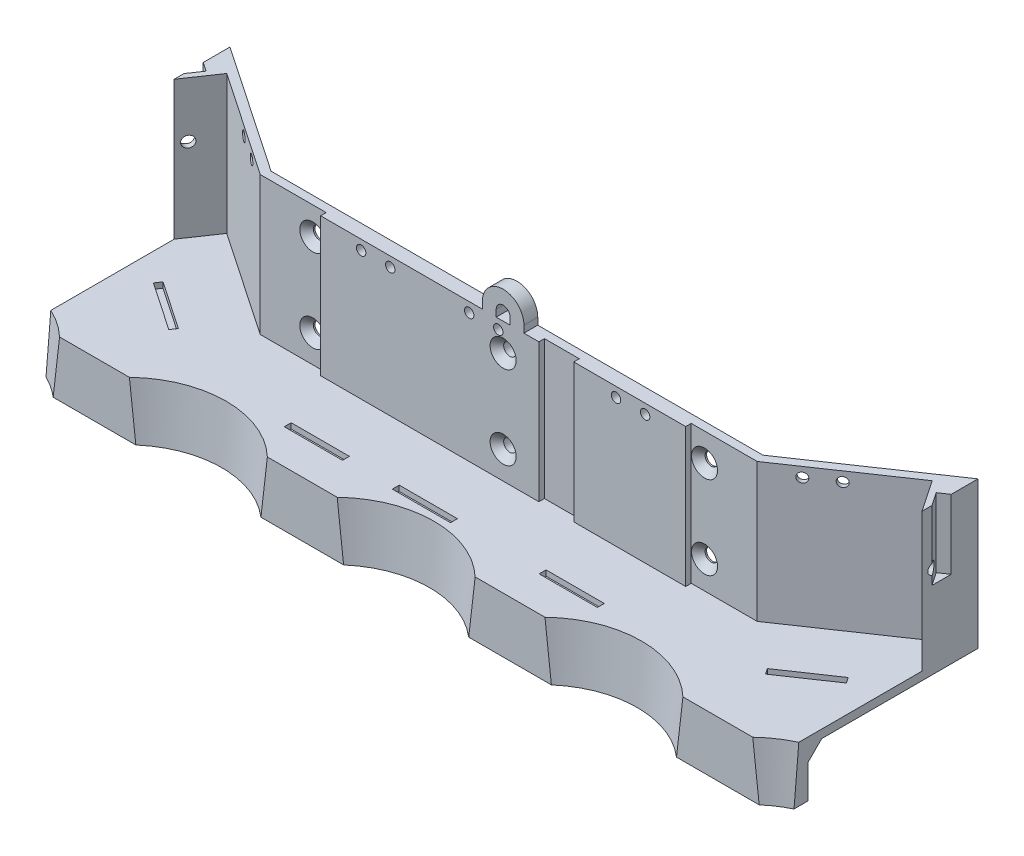
SolidWorks part; units mm, degrees
ref_plane "Front Plane" through (0, 0, 0) normal (0, 0, 1) x (1, 0, 0)
ref_plane "Top Plane" through (0, 0, 0) normal (0, 1, 0) x (1, 0, 0)
ref_plane "Right Plane" through (0, 0, 0) normal (1, 0, 0) x (0, 0, -1)
sketch "Sketch1" plane through (0, 0, 0) normal (1, 0, 0) x (0, 0, -1)
  line L0 (0, 0) -> (0, 53)
  line L1 (0, 53) -> (-3, 53)
  line L2 (-3, 53) -> (-3, 3)
  line L3 (-3, 3) -> (-40, 3)
  line L4 (-40, 3) -> (-40, 0)
  line L5 (-25, 0) -> (0, 0)
  line L6 (-40, 0) -> (-40, -17)
  line L7 (-40, -17) -> (-30, -17)
  line L9 (-25, 0) -> (-30, -5)
  line L10 (-30, -5) -> (-30, -17)
  dimension "D1" = 3
  dimension "D2" = 3
  dimension "D3" = 40
  dimension "D4" = 50
  dimension "D5" = 20
  dimension "D6" = 10
  dimension "D7" = 15
  dimension "D8" = 45
extrude "Boss-Extrude1" add sketch "Sketch1" along normal mid plane 270
sketch "Sketch2" plane through (0, 0, 0) normal (1, 0, 0) x (0, 0, -1)
  line L0 (-66, 3) -> (-66, -112) construction
  line L1 (-66, 3) -> (-30, 3)
  line L2 (-3, 3) -> (-40, 3) construction
  line L3 (-30, 3) -> (-39, -112)
  line L4 (-39, -112) -> (-66, -112)
  line L5 (-40, 3) -> (-40, -17) construction
  line L6 (-66, 3) -> (-66, -112)
  dimension "D1" = 54
  dimension "D2" = 72
  dimension "D3" = 115
  dimension "D4" = 10
revolve "Cut-Revolve1" cut sketch "Sketch2" angle 360 about L0
ref_plane "Plane1" through (75, 0, 0) normal (1, 0, 0) x (0, 0, -1)
sketch "Sketch3" plane through (75, 0, 0) normal (1, 0, 0) x (0, 0, -1)
  line L4 (-30, 3) -> (-66, 3)
  line L5 (-39, -112) -> (-30, 3)
  line L6 (-66, -112) -> (-39, -112)
  line L7 (-66, 3) -> (-66, -112)
  line L8 (-30, 3) -> (-66, 3)
  line L9 (-39, -112) -> (-30, 3)
  line L10 (-66, -112) -> (-39, -112)
  line L11 (-66, 3) -> (-66, -112)
  dimension "D1" = 0
revolve "Cut-Revolve2" cut sketch "Sketch3" angle 360 about L11
ref_plane "Plane2" through (150, 0, 0) normal (1, 0, 0) x (0, 0, -1)
sketch "Sketch4" plane through (150, 0, 0) normal (1, 0, 0) x (0, 0, -1)
  line L8 (-30, 3) -> (-66, 3)
  line L9 (-66, 3) -> (-66, -112)
  line L10 (-66, -112) -> (-39, -112)
  line L11 (-39, -112) -> (-30, 3)
  line L12 (-30, 3) -> (-66, 3)
  line L13 (-66, 3) -> (-66, -112)
  line L14 (-66, -112) -> (-39, -112)
  line L15 (-39, -112) -> (-30, 3)
  dimension "D1" = 0
revolve "Cut-Revolve3" cut sketch "Sketch4" angle 360 about L13
sketch "Sketch5" plane through (0, 3, 0) normal (0, 1, 0) x (1, 0, 0)
  line L0 (135, -3) -> (135, 27.7803)
  line L1 (135, -3) -> (135, -33.2739) construction
  line L2 (135, 27.7803) -> (77.0996, -11.5585) construction
  line L3 (77.0996, -11.5585) -> (77.0996, -3)
  line L4 (135, -3) -> (-135, -3) construction
  line L5 (77.0996, -3) -> (135, -3)
  line L6 (129.7686, -36.2226) -> (84.4272, -67.0285) construction
  line L7 (77.0996, -11.5585) -> (89.6963, -3)
  line L8 (84.3581, -3) -> (135, 31.4072)
  line L9 (135, 31.4072) -> (135, 27.7803)
  arc A0 (135, -33.2739) -> (125.1002, -40) centre (150, -66) ccw construction
  line M16 (135, -3) -> (-135, -3)
  dimension "D1" = 70
  dimension "D2" = 50
  dimension "D3" = 3
extrude "Boss-Extrude2" add sketch "Sketch5" along normal up to surface and the other way up to surface contours L0 L2 M16
sketch "Sketch7" plane through (0, 3, 0) normal (0, 1, 0) x (1, 0, 0)
  line L0 (89.6963, -3) -> (135, 27.7803)
  line L1 (135, 31.4072) -> (135, -3) construction
  line L2 (135, 27.7803) -> (135, -3)
  line L3 (135, -3) -> (89.6963, -3)
  line L5 (135, 31.4072) -> (88.7736, 0) construction
  dimension "D1" = 3
extrude "Cut-Extrude1" cut sketch "Sketch7" along normal up to surface (50 mm away) up to face at (17.7547, 53, -5.0814)
sketch "Sketch8" plane through (0, 3, 0) normal (0, 1, 0) x (1, 0, 0)
  line L0 (135, 27.7803) -> (127.3111, 22.5563)
  line L1 (89.6963, -3) -> (135, 27.7803) construction
  line L2 (127.3111, 22.5563) -> (135, 11.2394)
  line L3 (135, 27.7803) -> (135, -33.2739) construction
  line L4 (135, 11.2394) -> (135, 27.7803)
  line L5 (142.7813, -5.5516) -> (143.0488, -5.9454) construction
  dimension "D1" = 3
extrude "Boss-Extrude3" add sketch "Sketch8" along normal up to surface (50 mm away) up to face at (29.745, 53, -8.8646)
sketch "Sketch9" plane through (97.5883, 0, -66.3036) normal (-0.8271, 0, 0.562) x (0.562, 0, 0.8271)
  circle A0 centre (62.8892, 33) radius 2
  dimension "D1" = 4
extrude "Cut-Extrude2" cut sketch "Sketch9" against normal through all
sketch "Sketch10" plane through (97.5883, 0, -66.3036) normal (-0.8271, 0, 0.562) x (0.562, 0, 0.8271)
  line L0 (66.571, 53) -> (66.571, 3) construction
  line L1 (66.571, 28) -> (57.8892, 28)
  line L2 (66.571, 28) -> (66.571, 38)
  line L3 (66.571, 38) -> (57.8892, 38)
  line L4 (57.8892, 28) -> (57.8892, 38)
  circle A0 centre (62.8892, 33) radius 1.5 construction
  dimension "D3" = 5
  dimension "D1" = 5
  dimension "D2" = 5
extrude "Cut-Extrude3" cut sketch "Sketch10" against normal through all from offset 2 offset against normal yes
mirror "Mirror1" about plane through (0, 0, 0) normal (1, 0, 0) of "Cut-Extrude2", "Cut-Extrude3", "Boss-Extrude3", "Cut-Revolve3", "Cut-Revolve2", "Boss-Extrude2", "Cut-Extrude1"
sketch "Sketch11" plane through (0, 0, 3) normal (0, 0, 1) x (1, 0, 0)
  line L0 (-50.1002, 3) -> (-99.8998, 3) construction
  line L1 (-65.9, 3) -> (12.9, 3)
  line L2 (-65.9, 3) -> (-65.9, 53)
  line L3 (-65.9, 53) -> (12.9, 53)
  line L4 (12.9, 3) -> (12.9, 53)
  line L5 (-63.9, 9) -> (-63.9, 20) construction
  line L6 (10.9, 20) -> (10.9, 9) construction
  line L7 (89.6963, 53) -> (-89.6963, 53) construction
  line L8 (50.1002, 3) -> (24.8998, 3) construction
  line L9 (25.5, 3) -> (65.9, 3)
  line L10 (25.5, 3) -> (25.5, 53)
  line L11 (25.5, 53) -> (65.9, 53)
  line L12 (65.9, 3) -> (65.9, 53)
  line L13 (27.5, 7.25) -> (27.5, 38.75) construction
  line L14 (63.9, 20) -> (63.9, 9) construction
  dimension "D1" = 2
  dimension "D2" = 2
  dimension "D3" = 2
  dimension "D4" = 2
extrude "Boss-Extrude4" add sketch "Sketch11" along normal blind 2
sketch "Sketch15" plane through (0, 3, 0) normal (0, 1, 0) x (1, 0, 0)
  line L0 (-107.6969, -17.9719) -> (-125.067, -6.1703)
  line L1 (-107.6969, -17.9719) -> (-106.2919, -15.904)
  line L2 (-125.067, -6.1703) -> (-123.6621, -4.1024)
  line L3 (-106.2919, -15.904) -> (-123.6621, -4.1024)
  line L5 (-103.3969, -17.871) -> (-129.0385, -0.4495) construction
  line L6 (-97.3635, -9.8805) -> (-101.8594, -16.4977) construction
  line L7 (-127.8908, 3.9089) -> (-121.428, 13.4211) construction
  line L8 (-60, -25) -> (-29, -25) construction
  line L9 (-56.5, -25) -> (-35.5, -25)
  line L10 (-56.5, -25) -> (-56.5, -27.5)
  line L11 (-56.5, -27.5) -> (-35.5, -27.5)
  line L12 (-35.5, -25) -> (-35.5, -27.5)
  line L13 (7, -25) -> (-24, -25) construction
  line L14 (-17.5, -25) -> (3.5, -25)
  line L15 (-17.5, -25) -> (-17.5, -27.5)
  line L16 (-17.5, -27.5) -> (3.5, -27.5)
  line L17 (3.5, -25) -> (3.5, -27.5)
  line L18 (-27.5, -9.25) -> (-27.5, -20.75) construction
  line L19 (-60.5, -23) -> (-60.5, -15) construction
  line L20 (-25.5, -20.75) -> (-25.5, -9.25) construction
  line L22 (0, 0) -> (0, -30) construction
  line L23 (88.7736, 0) -> (-88.7736, 0) construction
  line L24 (35.5, -25) -> (35.5, -27.5)
  line L25 (56.5, -27.5) -> (35.5, -27.5)
  line L26 (56.5, -25) -> (56.5, -27.5)
  line L27 (56.5, -25) -> (35.5, -25)
  line L28 (106.2919, -15.904) -> (123.6621, -4.1024)
  line L29 (125.067, -6.1703) -> (123.6621, -4.1024)
  line L30 (107.6969, -17.9719) -> (106.2919, -15.904)
  line L31 (107.6969, -17.9719) -> (125.067, -6.1703)
  line L32 (7.5, -15) -> (7.5, -23) construction
  arc A0 (24.8998, -40) -> (-24.8998, -40) centre (0, -66) ccw construction
  dimension "D1" = 0
  dimension "D2" = 4
  dimension "D3" = 8
  dimension "D4" = 2.5
  dimension "D5" = 2.5
  dimension "D6" = 8
  dimension "D7" = 4
  dimension "D8" = 8
  dimension "D9" = 4
  dimension "D10" = 2.5
extrude "Cut-Extrude8" cut sketch "Sketch15" against normal blind 2
sketch "Sketch16" plane through (0, 0, 5) normal (0, 0, 1) x (1, 0, 0)
  line L0 (0, 0) -> (0, 53) construction
  line L1 (12.9, 53) -> (-65.9, 53) construction
  circle A0 centre (-1.75, 49.5) radius 1.5
  circle A2 centre (-12.25, 49.5) radius 1.5
  circle A4 centre (-40.75, 49.5) radius 1.5
  circle A5 centre (-51.25, 49.5) radius 1.5
  circle A6 centre (51.25, 49.5) radius 1.5
  circle A7 centre (40.75, 49.5) radius 1.5
  dimension "D1" = 3
extrude "Cut-Extrude9" cut sketch "Sketch16" against normal through all
sketch "Sketch17" plane through (-29.7228, 0, 43.7473) normal (-0.562, 0, 0.8271) x (0.8271, 0, 0.562)
  circle A0 centre (-94.7315, 49.5) radius 1.5
  circle A1 centre (-84.2315, 49.5) radius 1.5
  dimension "D1" = 3
extrude "Cut-Extrude10" cut sketch "Sketch17" against normal through all
mirror "Mirror2" about plane through (0, 0, 0) normal (1, 0, 0) of "Cut-Extrude10"
hole_wizard "CSK for M4 Countersunk Raised Head Screw1" positions "Sketch20" profile "Sketch21" countersink size "M4" standard "ISO" end condition through all
sketch "Sketch20" plane through (0, 0, 3) normal (0, 0, 1) x (1, 0, 0)
  line L0 (-89.6963, 53) -> (-89.6963, 3) construction
  line L1 (89.6963, 53) -> (89.6963, 3) construction
  line L2 (12.9, 53) -> (-65.9, 53) construction
  line L3 (-65.9, 3) -> (-89.6963, 3) construction
  line L5 (-70.6963, 43) -> (70.6963, 43) construction
  line L6 (-70.6963, 43) -> (-70.6963, 13) construction
  line L7 (-70.6963, 13) -> (70.6963, 13) construction
  line L8 (70.6963, 43) -> (70.6963, 13) construction
  point P0 (-70.6963, 43)
  point P2 (-70.6963, 13)
  point P4 (70.6963, 43)
  point P6 (70.6963, 13)
  dimension "D2" = 19
  dimension "D4" = 19
  dimension "D5" = 10
  dimension "D6" = 10
sketch "Sketch21" plane through (-70.6963, 43, 3) normal (1, 0, 0) x (0, -1, 0)
  line L0 (0, 0) -> (0, 34.4072)
  line L1 (0, 34.4072) -> (2.25, 34.4072)
  line L2 (2.25, 34.4072) -> (2.25, 2.45)
  line L3 (2.25, 2.45) -> (4.7, 0)
  line L5 (4.7, 0) -> (0, 0)
  line L6 (-2.25, 2.45) -> (-4.7, 0) construction
  line L11 (0, -6.35) -> (0, 107.95) construction
  dimension "Thru Hole Dia." = 4.5
  dimension "Thru Hole Depth" = 34.4072
  dimension "Near C'Sink Dia." = 9.4
  dimension "Near C'Sink Angle" = 90
sketch "Sketch23" plane through (0, 0, 5) normal (0, 0, 1) x (1, 0, 0)
  line L7 (0, 55.5) -> (0, 0) construction
  line L8 (-7.5, 53) -> (-7.5, 55.5)
  line L9 (12.9, 53) -> (-65.9, 53) construction
  line L10 (7.5, 55.5) -> (7.5, 53)
  line L11 (-2.5, 53) -> (-2.5, 55.5)
  line L12 (2.5, 55.5) -> (2.5, 53)
  line L13 (-7.5, 53) -> (-2.5, 53)
  line L14 (7.5, 53) -> (2.5, 53)
  arc A2 (-7.5, 55.5) -> (7.5, 55.5) centre (0, 55.5) cw
  arc A3 (-2.5, 55.5) -> (2.5, 55.5) centre (0, 55.5) cw
  dimension "D1" = 5
  dimension "D2" = 15
  dimension "D3" = 2.5
extrude "Boss-Extrude5" add sketch "Sketch23" against normal up to surface (5 mm away) up to face at (-68.4463, 43, 0)
sketch "Sketch24" plane through (0, 28, 0) normal (0, 1, 0) x (1, 0, 0)
  line L3 (135, 14.7983) -> (135, 21.7354)
  line L4 (135, 21.7354) -> (131.7753, 19.5445)
  line L5 (131.7753, 19.5445) -> (135, 14.7983)
  line L6 (135, 14.7983) -> (135, 21.7354)
  line L7 (135, 21.7354) -> (131.7753, 19.5445)
  line L8 (131.7753, 19.5445) -> (135, 14.7983)
  line L9 (-135, 21.7354) -> (-135, 14.7983)
  line L10 (-135, 14.7983) -> (-131.7753, 19.5445)
  line L11 (-131.7753, 19.5445) -> (-135, 21.7354)
  line L12 (-135, 21.7354) -> (-135, 14.7983)
  line L13 (-135, 14.7983) -> (-131.7753, 19.5445)
  line L14 (-131.7753, 19.5445) -> (-135, 21.7354)
  dimension "D1" = 0
  dimension "D2" = 0
extrude "Cut-Extrude11" cut sketch "Sketch24" along normal through all
hole_wizard "CSK for M4 Countersunk Raised Head Screw2" positions "Sketch28" profile "Sketch26" countersink size "M4" standard "ISO" end condition through all
sketch "Sketch28" plane through (0, 0, 5) normal (0, 0, 1) x (1, 0, 0)
  line L1 (-70.6963, 43) -> (70.6963, 43) construction
  line L2 (-70.6963, 43) -> (-70.6963, 13) construction
  line L3 (-70.6963, 13) -> (70.6963, 13) construction
  line L4 (70.6963, 43) -> (70.6963, 13) construction
  point P0 (0, 43)
  point P2 (0, 13)
sketch "Sketch26" plane through (0, 43, 5) normal (1, 0, 0) x (0, -1, 0)
  line L0 (0, 0) -> (0, 36.4072)
  line L1 (0, 36.4072) -> (2.25, 36.4072)
  line L2 (2.25, 36.4072) -> (2.25, 2.45)
  line L3 (2.25, 2.45) -> (4.7, 0)
  line L5 (4.7, 0) -> (0, 0)
  line L6 (-2.25, 2.45) -> (-4.7, 0) construction
  line L11 (0, -6.35) -> (0, 107.95) construction
  dimension "Thru Hole Dia." = 4.5
  dimension "Thru Hole Depth" = 36.4072
  dimension "Near C'Sink Dia." = 9.4
  dimension "Near C'Sink Angle" = 90
hole_wizard "CSK for M3 Countersunk Raised Head Screw1" positions "Sketch29" profile "Sketch30" countersink size "M3" standard "ISO" end condition through all
sketch "Sketch29" plane through (0, 0, 0) normal (0, 0, -1) x (-1, 0, 0)
  point P0 (-51.25, 49.5)
  point P3 (-40.75, 49.5)
  point P6 (1.75, 49.5)
  point P9 (12.25, 49.5)
  point P13 (40.75, 49.5)
  point P16 (51.25, 49.5)
sketch "Sketch30" plane through (51.25, 49.5, 0) normal (1, 0, 0) x (0, 1, 0)
  line L0 (0, 0) -> (0, 40)
  line L1 (0, 40) -> (1.7, 40)
  line L2 (1.7, 40) -> (1.7, 1.45)
  line L3 (1.7, 1.45) -> (3.15, 0)
  line L5 (3.15, 0) -> (0, 0)
  line L6 (-1.7, 1.45) -> (-3.15, 0) construction
  line L11 (0, -6.35) -> (0, 107.95) construction
  dimension "Thru Hole Dia." = 3.4
  dimension "Thru Hole Depth" = 40
  dimension "Near C'Sink Dia." = 6.3
  dimension "Near C'Sink Angle" = 90
hole_wizard "CSK for M3 Countersunk Raised Head Screw2" positions "Sketch31" profile "Sketch32" countersink size "M3" standard "ISO" end condition through all
sketch "Sketch31" plane through (-28.0369, 0, 41.2658) normal (0.562, 0, -0.8271) x (-0.8271, 0, -0.562)
  point P0 (84.2315, 49.5)
  point P3 (94.7315, 49.5)
sketch "Sketch32" plane through (-97.7089, 49.5, -6.0708) normal (0, 1, 0) x (-0.8271, 0, -0.562)
  line L0 (0, 0) -> (0, 59.0644)
  line L1 (0, 59.0644) -> (1.7, 59.0644)
  line L2 (1.7, 59.0644) -> (1.7, 1.45)
  line L3 (1.7, 1.45) -> (3.15, 0)
  line L5 (3.15, 0) -> (0, 0)
  line L6 (-1.7, 1.45) -> (-3.15, 0) construction
  line L11 (0, -6.35) -> (0, 107.95) construction
  dimension "Thru Hole Dia." = 3.4
  dimension "Thru Hole Depth" = 59.0644
  dimension "Near C'Sink Dia." = 6.3
  dimension "Near C'Sink Angle" = 90
mirror "Mirror3" about plane through (0, 0, 0) normal (1, 0, 0) of "CSK for M3 Countersunk Raised Head Screw2"
